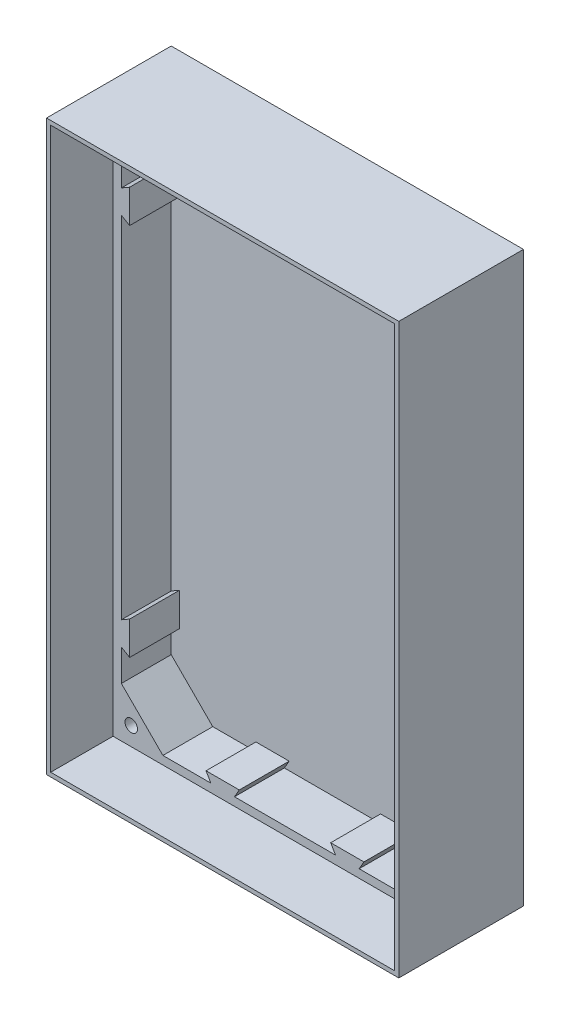
SolidWorks part; units mm, degrees
ref_plane "Alzado" through (0, 0, 0) normal (1, 0, 0) x (0, 1, 0)
ref_plane "Planta" through (0, 0, 0) normal (0, 0, 1) x (0, 1, 0)
ref_plane "Vista lateral" through (0, 0, 0) normal (0, 1, 0) x (-1, 0, 0)
sketch "Croquis2" plane through (0, 0, 0) normal (0, 0, 1) x (0, 1, 0)
  line L1 (-68.4243, -42.383) -> (68.4243, -42.383)
  line L2 (-68.4243, -42.383) -> (-68.4243, 42.383)
  line L3 (-68.4243, 42.383) -> (68.4243, 42.383)
  line L4 (68.4243, -42.383) -> (68.4243, 42.383)
  line L5 (-68.4243, -42.383) -> (68.4243, 42.383) construction
  line L6 (-68.4243, 42.383) -> (68.4243, -42.383) construction
  point P0 (0, 0)
extrude "Saliente-Extruir1" add sketch "Croquis2" along normal mid plane 30
sketch "Croquis3" plane through (0, 0, 0) normal (0, 0, 1) x (0, 1, 0)
  line L0 (68.4243, -42.383) -> (68.4243, 42.383) construction
  line L1 (-55.4243, -39.383) -> (-47.8453, -39.383)
  line L2 (-65.4243, -29.383) -> (-65.4243, -17.8453)
  line L3 (-55.4243, 39.383) -> (-47.8453, 39.383)
  line L4 (65.4243, -29.383) -> (65.4243, -17.8453)
  line L5 (-65.4243, -39.383) -> (65.4243, 39.383) construction
  line L6 (-65.4243, 39.383) -> (65.4243, -39.383) construction
  line L7 (68.4243, 42.383) -> (-68.4243, 42.383) construction
  line L8 (-65.4243, 29.383) -> (-55.4243, 39.383)
  line L9 (55.4243, 39.383) -> (65.4243, 29.383)
  line L10 (55.4243, -39.383) -> (65.4243, -29.383)
  line L11 (-65.4243, -29.383) -> (-55.4243, -39.383)
  line L12 (-63.4243, 19) -> (-63.4243, 11)
  line L13 (-63.4243, 19) -> (-65.4243, 17.8453)
  line L14 (-63.4243, 11) -> (-65.4243, 12.1547)
  line L15 (-49, 37.383) -> (-41, 37.383)
  line L16 (-41, 37.383) -> (-42.1547, 39.383)
  line L17 (-49, 37.383) -> (-47.8453, 39.383)
  line L18 (0, -16.5) -> (0, 16.5) construction
  line L19 (-16.5, 0) -> (16.5, 0) construction
  line L20 (-63.4243, -11) -> (-65.4243, -12.1547)
  line L21 (-63.4243, -19) -> (-63.4243, -11)
  line L22 (-63.4243, -19) -> (-65.4243, -17.8453)
  line L23 (41, 37.383) -> (42.1547, 39.383)
  line L24 (49, 37.383) -> (41, 37.383)
  line L25 (49, 37.383) -> (47.8453, 39.383)
  line L26 (67.4243, -19) -> (65.4243, -17.8453)
  line L27 (67.4243, -19) -> (67.4243, -11)
  line L28 (67.4243, -11) -> (65.4243, -12.1547)
  line L29 (67.4243, 11) -> (65.4243, 12.1547)
  line L30 (67.4243, 19) -> (67.4243, 11)
  line L31 (67.4243, 19) -> (65.4243, 17.8453)
  line L32 (-42.1547, -39.383) -> (42.1547, -39.383)
  line L33 (47.8453, -39.383) -> (55.4243, -39.383)
  line L34 (65.4243, -12.1547) -> (65.4243, 12.1547)
  line L35 (65.4243, 17.8453) -> (65.4243, 29.383)
  line L36 (47.8453, 39.383) -> (55.4243, 39.383)
  line L37 (-42.1547, 39.383) -> (42.1547, 39.383)
  line L38 (49, -41.383) -> (47.8453, -39.383)
  line L39 (49, -41.383) -> (41, -41.383)
  line L40 (41, -41.383) -> (42.1547, -39.383)
  line L41 (-41, -41.383) -> (-42.1547, -39.383)
  line L42 (-49, -41.383) -> (-47.8453, -39.383)
  line L43 (-49, -41.383) -> (-41, -41.383)
  line L44 (-65.4243, 17.8453) -> (-65.4243, 29.383)
  line L45 (-65.4243, -12.1547) -> (-65.4243, 12.1547)
  point P0 (0, 0)
  point P24 (-45, 37.383)
  point P29 (-63.4243, 15)
  point P56 (-65.4243, 17.2679)
  dimension "D1" = 3
  dimension "D2" = 3
  dimension "D3" = 2
  dimension "D4" = 60
  dimension "D9" = 60
  dimension "D10" = 8
  dimension "D11" = 2
  dimension "D12" = 60
  dimension "D13" = 60
  dimension "D14" = 8
  dimension "D15" = 45
  dimension "D16" = 15
  dimension "D17" = 2
  dimension "D18" = 60
  dimension "D19" = 60
  dimension "D20" = 8
  dimension "D21" = 8
  dimension "D22" = 60
  dimension "D23" = 60
  dimension "D24" = 2
  dimension "D25" = 2
  dimension "D26" = 2
  dimension "D27" = 60
  dimension "D28" = 60
  dimension "D29" = 60
  dimension "D30" = 60
  dimension "D31" = 8
  dimension "D32" = 8
extrude "Cortar-Extruir1" cut sketch "Croquis3" against normal blind 27 from surface at 15 starting at face at (0, 0, 15)
sketch "Croquis4" plane through (0, 0, 15) normal (0, 0, 1) x (1, 0, 0)
  line L0 (42.383, 68.4243) -> (-42.383, 68.4243) construction
  line L1 (-41.383, -67.4243) -> (41.383, -67.4243)
  line L2 (-41.383, -67.4243) -> (-41.383, 67.4243)
  line L3 (-41.383, 67.4243) -> (41.383, 67.4243)
  line L4 (41.383, -67.4243) -> (41.383, 67.4243)
  line L5 (-41.383, -67.4243) -> (41.383, 67.4243) construction
  line L6 (-41.383, 67.4243) -> (41.383, -67.4243) construction
  line L7 (-42.383, 68.4243) -> (-42.383, -68.4243) construction
  point P0 (0, 0)
  dimension "D1" = 1
  dimension "D2" = 1
extrude "Cortar-Extruir2" cut sketch "Croquis4" against normal blind 15
sketch "Croquis6" plane through (0, 0, 0) normal (0, 0, 1) x (1, 0, 0)
  line L3 (0, -16.5) -> (0, 16.5) construction
  line L5 (16.5, 0) -> (-16.5, 0) construction
  circle A0 centre (-37, 63) radius 1.5
  circle A1 centre (37, 63) radius 1.5
  circle A2 centre (37, -63) radius 1.5
  circle A3 centre (-37, -63) radius 1.5
  dimension "D1" = 3
  dimension "D2" = 63
  dimension "D3" = 37
extrude "Cortar-Extruir3" cut sketch "Croquis6" against normal blind 10 from surface at 0 starting at face at (-12.8722, -23.0229, 0)
